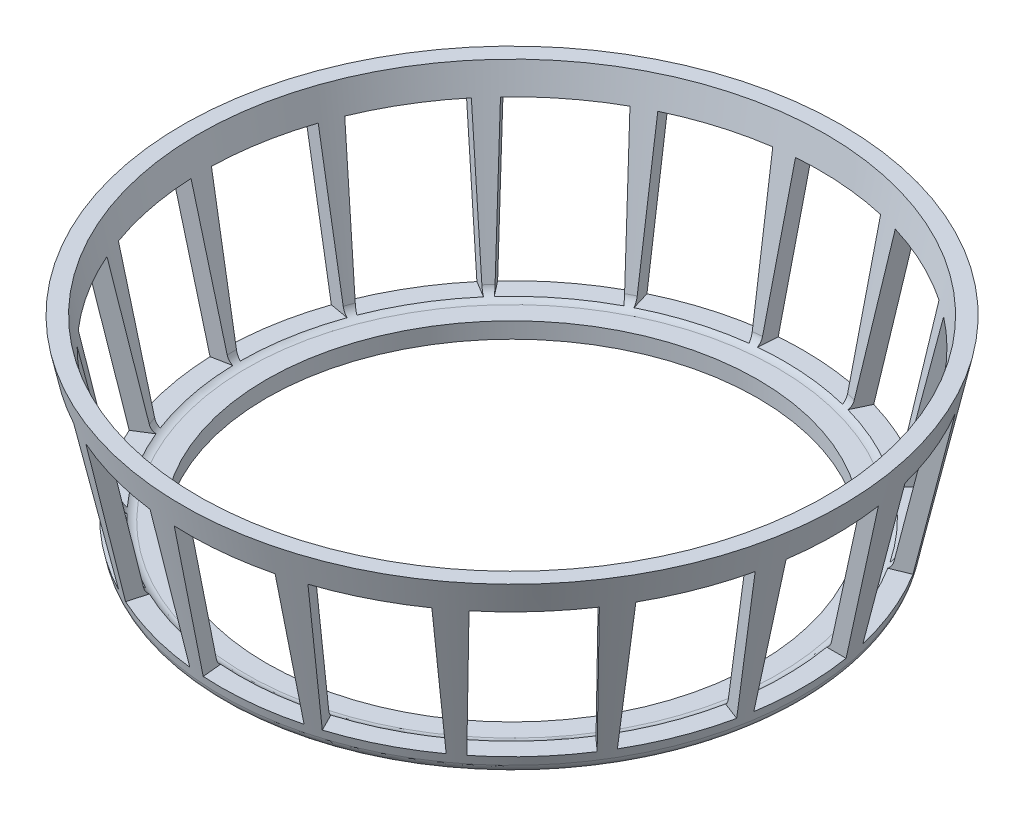
SolidWorks part; units mm, degrees
ref_plane "Ön Düzlem" through (0, 0, 0) normal (0, 0, 1) x (1, 0, 0)
ref_plane "Üst Düzlem" through (0, 0, 0) normal (0, 1, 0) x (1, 0, 0)
ref_plane "Sağ Düzlem" through (0, 0, 0) normal (1, 0, 0) x (0, 0, -1)
sketch "Çizim1" plane through (0, 0, 0) normal (0, 0, 1) x (1, 0, 0)
  line L0 (-26.17, 16.23) -> (-23.127, 2.1192)
  line L2 (-24.1702, 0.7892) -> (-27.5, 16.23)
  line L3 (-27.5, 16.23) -> (-26.17, 16.23)
  line L4 (0, 0) -> (0, 42.4771) construction
  line L5 (-22.1495, 1.33) -> (-20.5, 1.33)
  line L6 (-20.5, 1.33) -> (-20.5, 0)
  line L7 (-20.5, 0) -> (-23.1927, 0)
  arc A0 (-22.1495, 1.33) -> (-23.127, 2.1192) centre (-22.1495, 2.33) cw
  arc A1 (-23.1927, 0) -> (-24.1702, 0.7892) centre (-23.1927, 1) cw
  point P13 (-24, 0)
  dimension "D6" = 1
  dimension "D1" = 27.5
  dimension "D2" = 1.33
  dimension "D3" = 24
  dimension "D4" = 3.5
  dimension "D5" = 1.33
revolve "Döndür1" add sketch "Çizim1" angle 360 about L4
sketch "Çizim3" plane through (0, 0, 0) normal (0, 0, 1) x (1, 0, 0)
  line L0 (26.17, 16.23) -> (-26.17, 16.23) construction
  line L1 (19.6801, 13.87) -> (31.9244, 13.87)
  line L2 (19.6801, 13.87) -> (19.6801, 1.52)
  line L3 (19.6801, 1.52) -> (31.9244, 1.52)
  line L4 (31.9244, 13.87) -> (31.9244, 1.52)
  dimension "D1" = 2.36
  dimension "D2" = 12.35
extrude "Kes-Ekstrüzyon1" cut sketch "Çizim3" against normal mid plane 7.7
pattern_circular "Dairesel Kaplama1" count 17 every 21.1 about axis through (0, 0, 0) along (0, 1, 0) of "Kes-Ekstrüzyon1"
